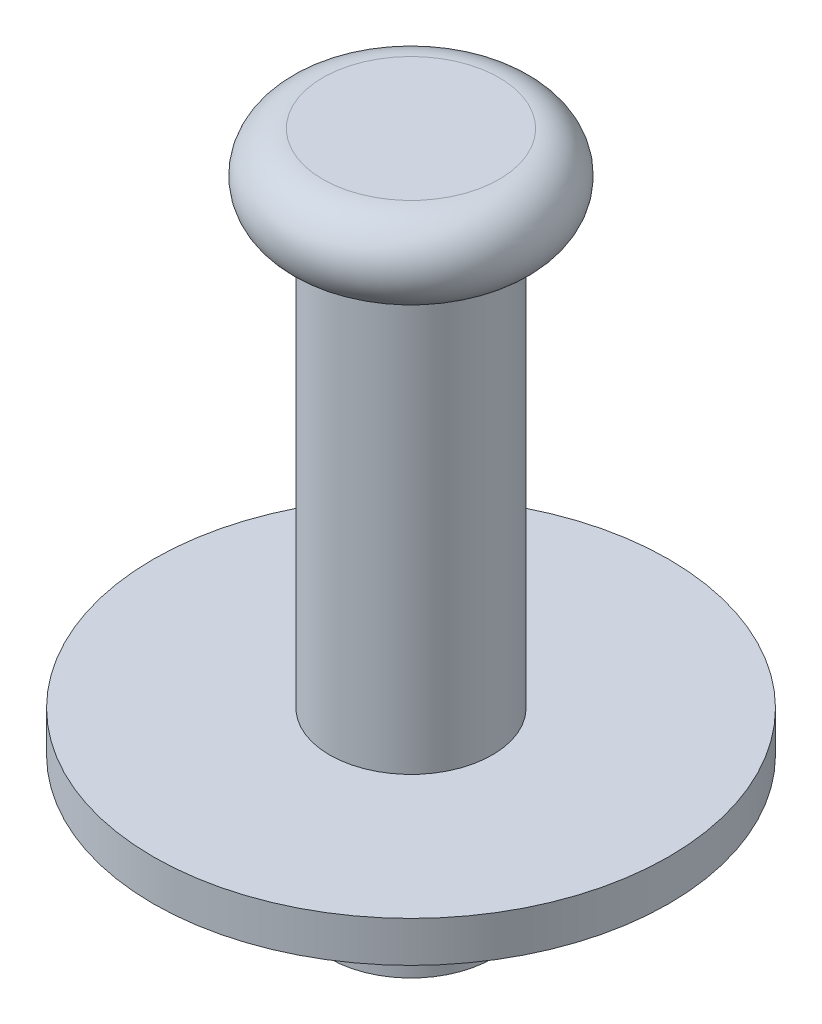
SolidWorks part; units mm, degrees
ref_plane "Спереди" through (0, 0, 0) normal (0, 0, 1) x (1, 0, 0)
ref_plane "Сверху" through (0, 0, 0) normal (0, 1, 0) x (1, 0, 0)
ref_plane "Справа" through (0, 0, 0) normal (1, 0, 0) x (0, 0, -1)
sketch "Эскиз1" plane through (0, 0, 0) normal (0, 0, 1) x (1, 0, 0)
  line L0 (0, 15.674) -> (0, -14.3417) construction
  line L2 (3, 12.3078) -> (3, -3.1922)
  line L3 (3, -3.1922) -> (9.5, -3.1922)
  line L4 (9.5, -3.1922) -> (9.5, -4.6922)
  line L5 (9.5, -4.6922) -> (3, -4.6922)
  line L6 (3, -4.6922) -> (3, -9.6922)
  line L7 (3, -9.6922) -> (0, -9.6922)
  line L8 (0, 15.3078) -> (3.25, 15.3078)
  line L9 (0, -9.6922) -> (0, 15.3078)
  line L10 (3.25, 12.3078) -> (3, 12.3078)
  arc A1 (3.25, 12.3078) -> (3.25, 15.3078) centre (3.25, 13.8078) ccw
  point P12 (6.25, -3.1922)
  dimension "D7" = 3
  dimension "D3" = 6
  dimension "D4" = 19
  dimension "D5" = 5
revolve "Повернуть2" add sketch "Эскиз1" angle 360 about L0
